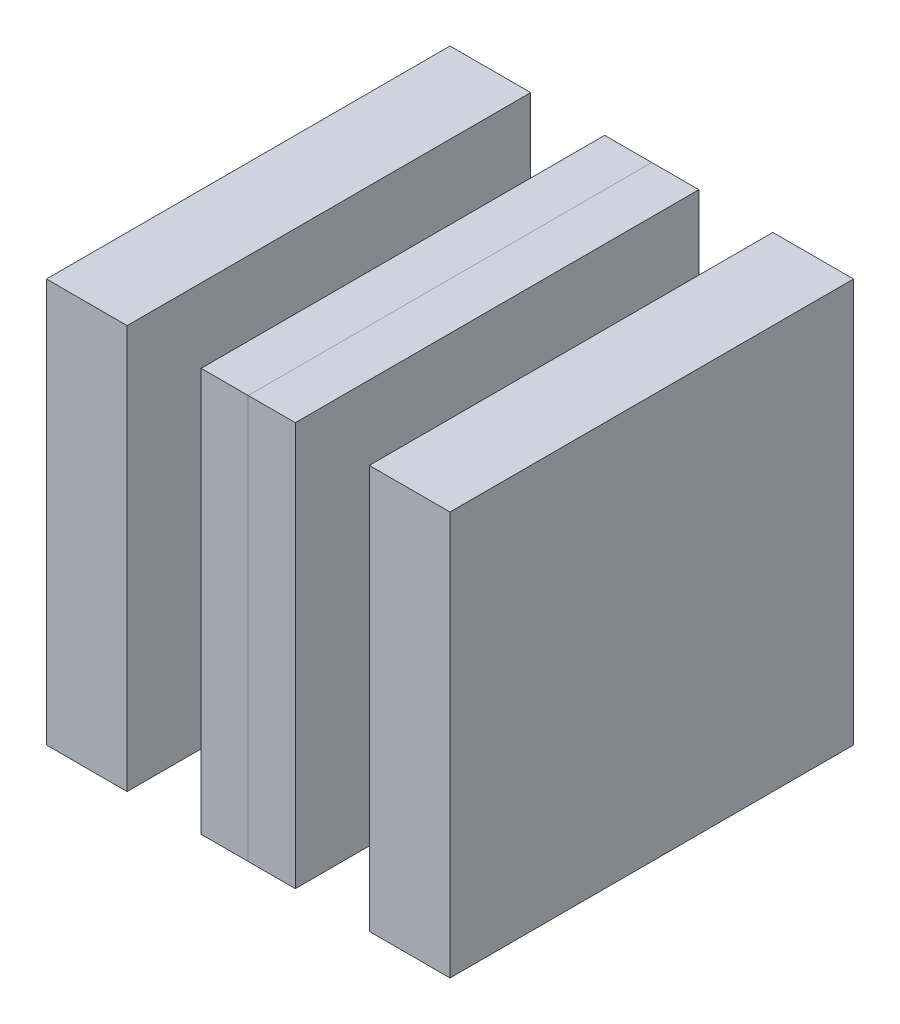
SolidWorks part; units mm, degrees
ref_plane "Front Plane" through (0, 0, 0) normal (0, 0, 1) x (1, 0, 0)
ref_plane "Top Plane" through (0, 0, 0) normal (0, 1, 0) x (1, 0, 0)
ref_plane "Right Plane" through (0, 0, 0) normal (1, 0, 0) x (0, 0, -1)
sketch "Sketch1" plane through (0, 0, 0) normal (0, 0, 1) x (1, 0, 0)
  line L1 (0, 0) -> (3, 0)
  line L2 (0, 0) -> (0, 15)
  line L3 (0, 15) -> (3, 15)
  line L4 (3, 0) -> (3, 15)
  line L5 (5.75, 15) -> (7.5, 15)
  line L6 (5.75, 15) -> (5.75, 0)
  line L7 (5.75, 0) -> (7.5, 0)
  line L8 (7.5, 15) -> (7.5, 0)
  dimension "D1" = 15
  dimension "D2" = 1.75
  dimension "D3" = 4.5
  dimension "D4" = 7.5
extrude "Boss-Extrude1" add sketch "Sketch1" along normal blind 15
mirror "Mirror1" about plane through (7.5, 15, 15) normal (-1, 0, 0) of bodies 102 101
